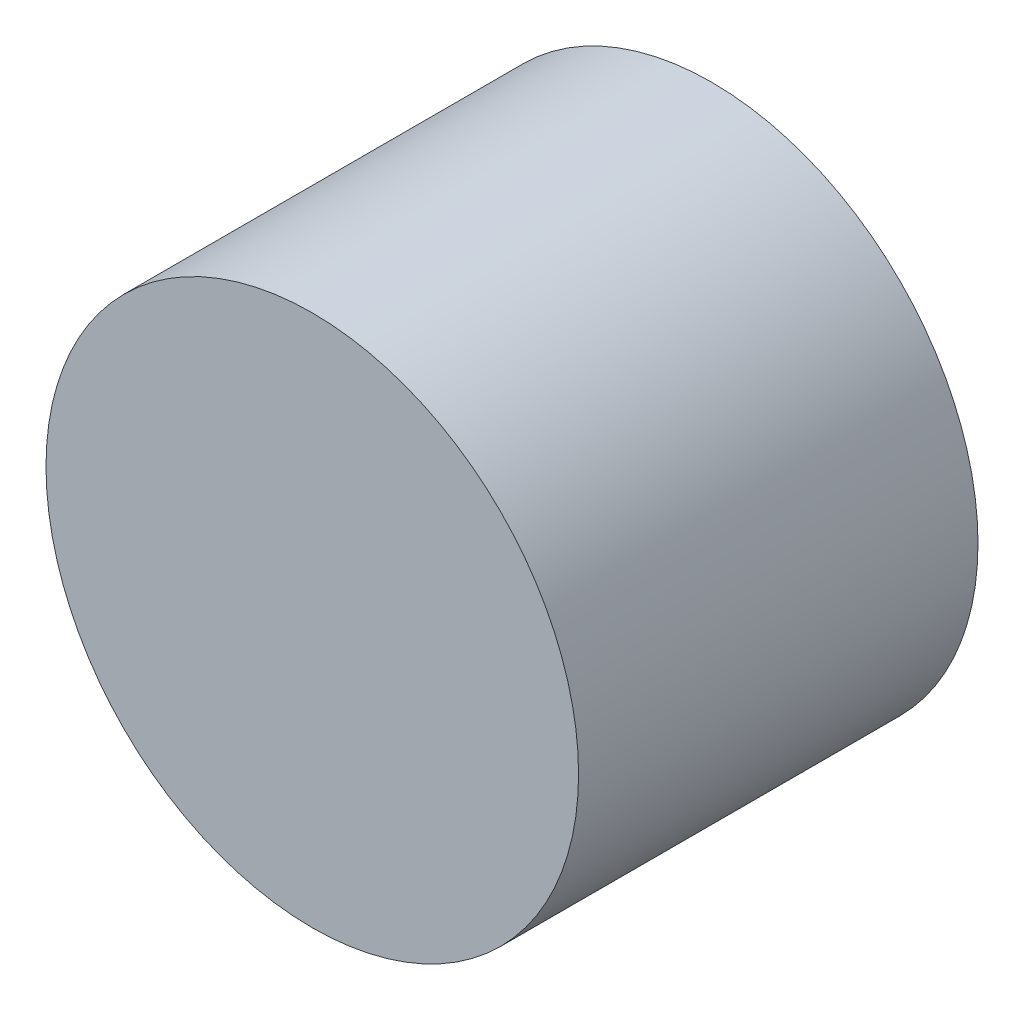
SolidWorks part; units mm, degrees
ref_plane "Front Plane" through (0, 0, 0) normal (0, 0, 1) x (1, 0, 0)
ref_plane "Top Plane" through (0, 0, 0) normal (0, 1, 0) x (1, 0, 0)
ref_plane "Right Plane" through (0, 0, 0) normal (1, 0, 0) x (0, 0, -1)
sketch "Sketch1" plane through (0, 0, 0) normal (0, 0, 1) x (1, 0, 0)
  circle A0 centre (0, 0) radius 30
extrude "Boss-Extrude1" add sketch "Sketch1" along normal blind 45
